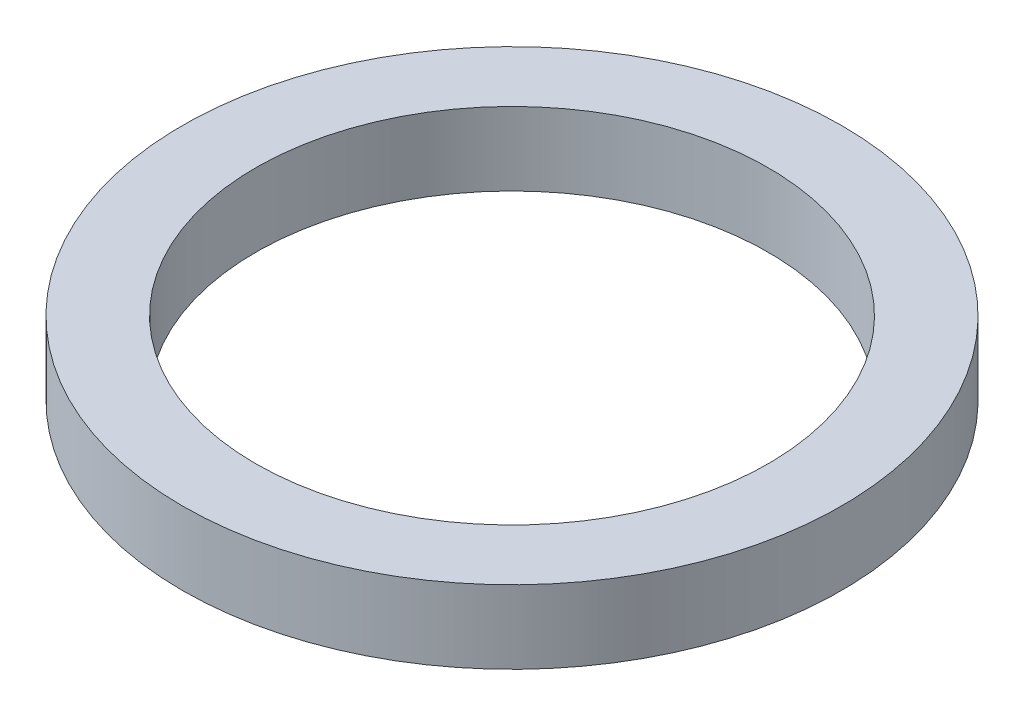
SolidWorks part; units mm, degrees
ref_plane "Front Plane" through (0, 0, 0) normal (0, 0, 1) x (1, 0, 0)
ref_plane "Top Plane" through (0, 0, 0) normal (0, 1, 0) x (1, 0, 0)
ref_plane "Right Plane" through (0, 0, 0) normal (1, 0, 0) x (0, 0, -1)
sketch "Sketch1" plane through (0, 0, 0) normal (0, 1, 0) x (1, 0, 0)
  circle A0 centre (0, 0) radius 22.5
  circle A1 centre (0, 0) radius 17.5
  dimension "D1" = 45
  dimension "D2" = 35
extrude "Boss-Extrude1" add sketch "Sketch1" along normal blind 5
